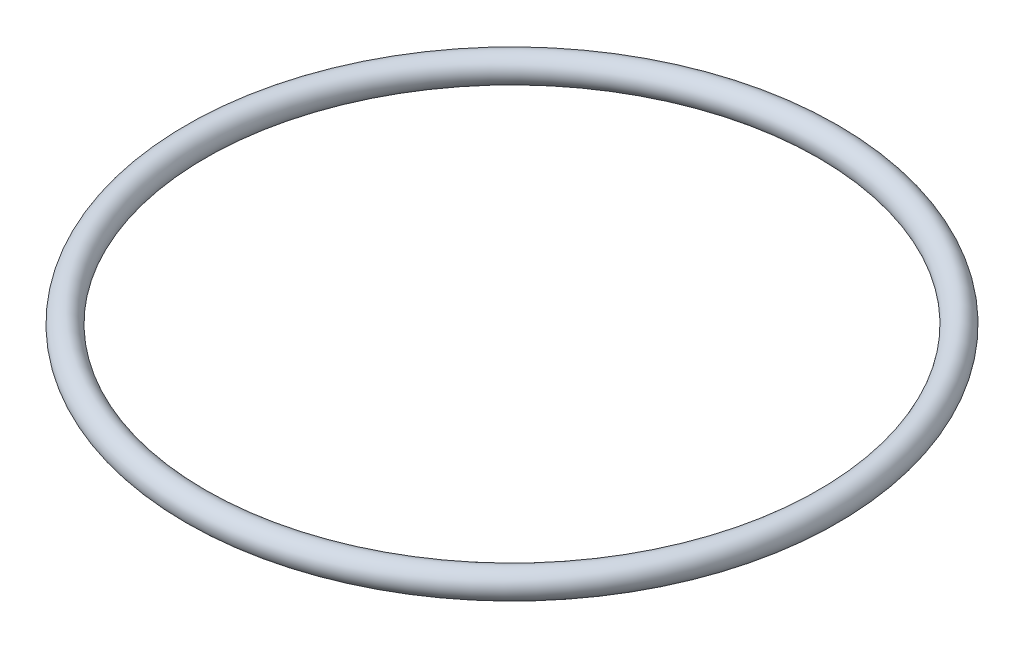
SolidWorks part; units mm, degrees
ref_plane "Front Plane" through (0, 0, 0) normal (0, 0, 1) x (1, 0, 0)
ref_plane "Top Plane" through (0, 0, 0) normal (0, 1, 0) x (1, 0, 0)
ref_plane "Right Plane" through (0, 0, 0) normal (1, 0, 0) x (0, 0, -1)
sketch "Sketch1" plane through (0, 0, 0) normal (0, 0, 1) x (1, 0, 0)
  line L0 (0, 0) -> (0, 26.4594) construction
  circle A0 centre (37.3062, 0) radius 1.5875
  point P5 (0, 0)
  dimension "D1" = 3.175
  dimension "D2" = 74.6125
revolve "Revolve1" add sketch "Sketch1" angle 360 about L0
